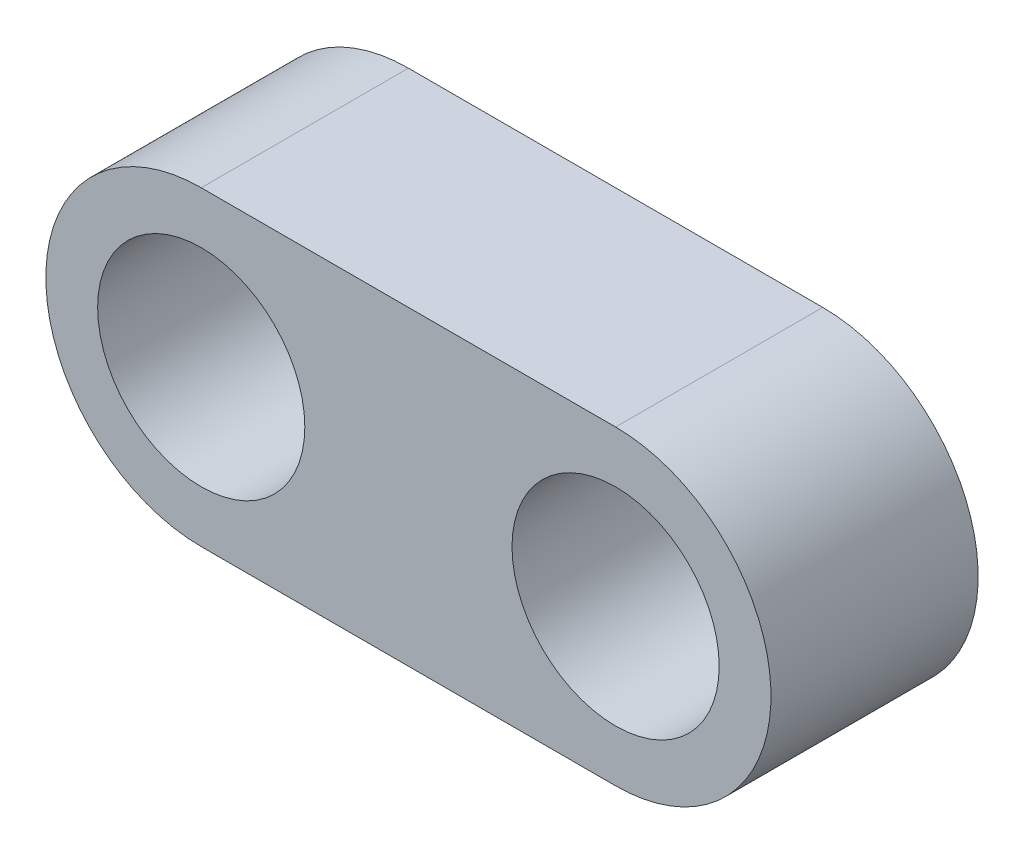
SolidWorks part; units mm, degrees
ref_plane "Front Plane" through (0, 0, 0) normal (0, 0, 1) x (1, 0, 0)
ref_plane "Top Plane" through (0, 0, 0) normal (0, 1, 0) x (1, 0, 0)
ref_plane "Right Plane" through (0, 0, 0) normal (1, 0, 0) x (0, 0, -1)
sketch "Sketch1" plane through (0, 0, 0) normal (0, 0, 1) x (1, 0, 0)
  line L0 (0, 0) -> (-2, 0) construction
  line L1 (0, 0) -> (2, 0) construction
  line L2 (-2, -1.5) -> (2, -1.5)
  line L3 (-2, 1.5) -> (2, 1.5)
  circle A0 centre (-2, 0) radius 1.5
  circle A1 centre (2, 0) radius 1.5
  circle A2 centre (-2, 0) radius 1
  circle A3 centre (2, 0) radius 1
  dimension "D2" = 3
  dimension "D3" = 2
  dimension "D1" = 2
extrude "Boss-Extrude1" add sketch "Sketch1" along normal blind 2 contours A0 A2 | A1 L3 A0 L2 | A1 A3
